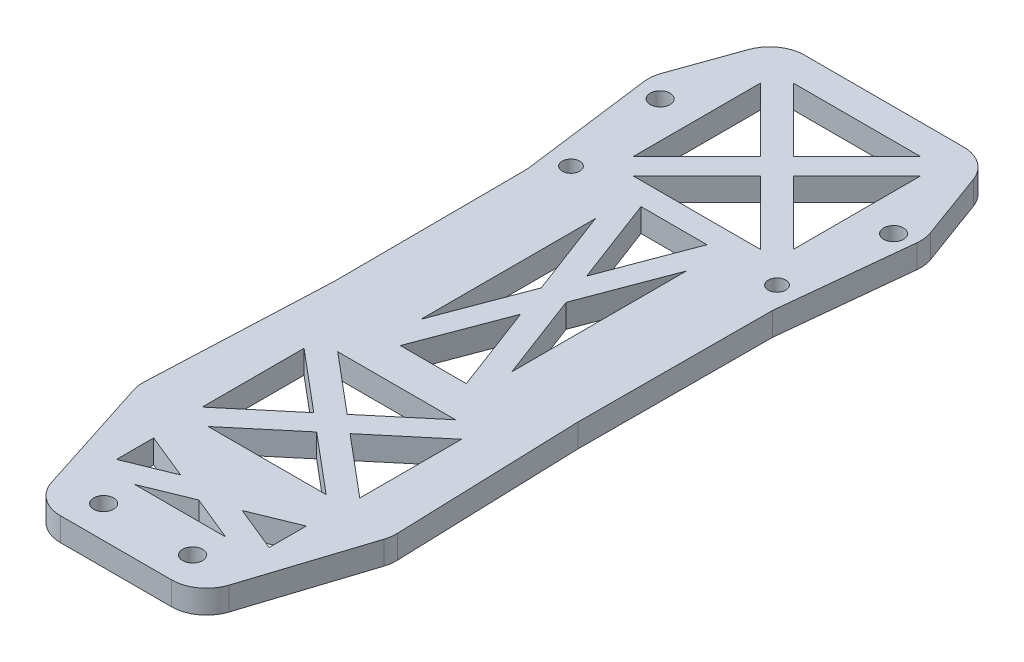
SolidWorks part; units mm, degrees
ref_plane "Front Plane" through (0, 0, 0) normal (0, 0, 1) x (1, 0, 0)
ref_plane "Top Plane" through (0, 0, 0) normal (0, 1, 0) x (1, 0, 0)
ref_plane "Right Plane" through (0, 0, 0) normal (1, 0, 0) x (0, 0, -1)
sketch "Sketch1" plane through (0, 0, 0) normal (0, 1, 0) x (1, 0, 0)
  line L12 (-13.5, 28.2668) -> (-13.5, 45.7228)
  line L13 (-13.5, 45.7228) -> (-3.1095, 36.9948)
  line L14 (-13.5, 28.2668) -> (-3.1095, 36.9948)
  line L15 (-10.1048, 48.0948) -> (0, 39.6068)
  line L16 (0, 39.6068) -> (10.1048, 48.0948)
  line L17 (-10.1048, 48.0948) -> (10.1048, 48.0948)
  line L18 (13.5, 28.2668) -> (13.5, 45.7228)
  line L19 (3.1095, 36.9948) -> (13.5, 45.7228)
  line L20 (3.1095, 36.9948) -> (13.5, 28.2668)
  line L21 (0, 34.3828) -> (10.1048, 25.8948)
  line L22 (-10.1048, 25.8948) -> (0, 34.3828)
  line L23 (-10.1048, 25.8948) -> (10.1048, 25.8948)
  line L24 (-13.0763, 19.5304) -> (-13.0763, 13.1591)
  line L25 (-13.0763, 13.1591) -> (-5.2847, 16.3448)
  line L26 (-13.0763, 19.5304) -> (-5.2847, 16.3448)
  line L27 (5.2847, 16.3448) -> (13.0763, 19.5304)
  line L28 (13.0763, 19.5304) -> (13.0763, 13.1591)
  line L29 (5.2847, 16.3448) -> (13.0763, 13.1591)
  line L30 (-7.7916, 10.9984) -> (0, 14.184)
  line L31 (0, 14.184) -> (7.7916, 10.9984)
  line L32 (-7.7916, 10.9984) -> (7.7916, 10.9984)
  line L33 (13.75, 102.3232) -> (13.75, 124.1664)
  line L34 (2.8284, 113.2448) -> (13.75, 124.1664)
  line L35 (13.75, 102.3232) -> (2.8284, 113.2448)
  line L36 (-10.9216, 99.4948) -> (10.9216, 99.4948)
  line L37 (-10.9216, 99.4948) -> (0, 110.4164)
  line L38 (10.9216, 99.4948) -> (0, 110.4164)
  line L39 (-13.75, 102.3232) -> (-2.8284, 113.2448)
  line L40 (-2.8284, 113.2448) -> (-13.75, 124.1664)
  line L41 (-13.75, 102.3232) -> (-13.75, 124.1664)
  line L42 (0, 116.0732) -> (-10.9216, 126.9948)
  line L43 (-10.9216, 126.9948) -> (10.9216, 126.9948)
  line L44 (0, 116.0732) -> (10.9216, 126.9948)
  line L45 (-7.7916, 89.9581) -> (-2.138, 74.9948)
  line L46 (-5.6536, 54.3729) -> (5.6536, 54.3729)
  line L47 (-7.7916, 60.0315) -> (-7.7916, 89.9581)
  line L48 (-5.6536, 95.6167) -> (5.6536, 95.6167)
  line L49 (7.7916, 60.0315) -> (7.7916, 89.9581)
  line L50 (-7.7916, 54.3729) -> (7.7916, 95.6167) construction
  line L51 (-7.7916, 95.6167) -> (7.7916, 54.3729) construction
  line L52 (-5.6536, 54.3729) -> (0, 69.3362)
  line L53 (-5.6536, 95.6167) -> (0, 80.6534)
  line L54 (-7.7916, 60.0315) -> (-2.138, 74.9948)
  line L55 (-5.9207, 96.3236) -> (9.6625, 55.0798) construction
  line L56 (-9.6625, 94.9098) -> (5.9207, 53.666) construction
  line L57 (-9.6625, 55.0798) -> (5.9207, 96.3236) construction
  line L58 (-5.9207, 53.666) -> (9.6625, 94.9098) construction
  line L59 (0, 69.3362) -> (5.6536, 54.3729)
  line L60 (2.138, 74.9948) -> (7.7916, 89.9581)
  line L61 (2.138, 74.9948) -> (7.7916, 60.0315)
  line L62 (0, 80.6534) -> (5.6536, 95.6167)
  line L63 (-9.5155, 0) -> (9.5155, 0)
  line L64 (-20, -0.0052) -> (20, 149.9948) construction
  line L65 (-20, 149.9948) -> (20, -0.0052) construction
  line L66 (-14.1084, 132.1078) -> (13.1312, 132.1078)
  line L69 (-19.7604, 128.1216) -> (-23.659, 117.1793)
  line L71 (-15.2273, 4.1627) -> (-21.92, 24.9687)
  line L73 (15.2273, 4.1627) -> (21.6746, 24.2059)
  line L76 (18.7641, 128.1742) -> (23.0196, 116.5735)
  line L77 (-23.9568, 114.391) -> (-20.9718, 91.4604)
  line L78 (21.0264, 91.4907) -> (23.3545, 113.8868)
  line L79 (21.9596, 26.2406) -> (20.9055, 58.256)
  line L80 (-22.2025, 27.0668) -> (-20.8394, 58.396)
  line L81 (-20.8394, 58.396) -> (-20.9718, 91.4604)
  line L82 (20.9055, 58.256) -> (21.0264, 91.4907)
  circle A4 centre (-20, 113.2448) radius 1.7
  circle A5 centre (20, 113.2448) radius 1.7
  circle A6 centre (7.62, 5.4973) radius 1.7
  circle A7 centre (-7.62, 5.4973) radius 1.7
  arc A12 (-14.1084, 132.1078) -> (-19.7604, 128.1216) centre (-14.1084, 126.1078) ccw
  arc A13 (13.1312, 132.1078) -> (18.7641, 128.1742) centre (13.1312, 126.1078) cw
  arc A14 (15.2273, 4.1627) -> (9.5155, 0) centre (9.5155, 6) cw
  arc A15 (-15.2273, 4.1627) -> (-9.5155, 0) centre (-9.5155, 6) ccw
  arc A16 (21.9596, 26.2406) -> (21.6746, 24.2059) centre (15.9628, 26.0432) cw
  arc A17 (-22.2025, 27.0668) -> (-21.92, 24.9687) centre (-16.2082, 26.806) ccw
  arc A20 (23.3545, 113.8868) -> (23.0196, 116.5735) centre (17.3867, 114.5071) ccw
  arc A23 (-23.9568, 114.391) -> (-23.659, 117.1793) centre (-18.007, 115.1656) cw
  point P70 (0, 74.9948)
  dimension "D1" = 2
  dimension "D2" = 2
extrude "Boss-Extrude1" add sketch "Sketch1" along normal blind 4
sketch "Sketch2" plane through (0, 4, 0) normal (0, 1, 0) x (1, 0, 0)
  point P0 (-7.62, 5.4973)
  point P2 (7.62, 5.4973)
  point P4 (20, 113.2448)
  point P6 (-20, 113.2448)
hole_wizard "M3 Clearance Hole1" positions "Sketch2" profile "Sketch3" hole size "M3" standard "ISO" end condition through all
sketch "Sketch3" plane through (-7.62, 4, -5.4973) normal (1, 0, 0) x (0, 0, 1)
  line L0 (0, 0) -> (0, 4)
  line L1 (0, 4) -> (1.7, 4)
  line L2 (1.7, 4) -> (1.7, 0)
  line L5 (1.7, 0) -> (0, 0)
  line L11 (0, -6.35) -> (0, 107.95) construction
  dimension "Thru Hole Dia." = 3.4
  dimension "Thru Hole Depth" = 4
sketch "Sketch4" plane through (0, 4, 0) normal (0, 1, 0) x (1, 0, 0)
  line L0 (-5.6536, 95.6167) -> (-17.6536, 95.6167) construction
  line L1 (5.6536, 95.6167) -> (17.6536, 95.6167) construction
  line L2 (-5.6536, 95.6167) -> (5.6536, 95.6167) construction
  line L3 (0, 80.6534) -> (5.6536, 95.6167) construction
  circle A0 centre (-17.6536, 95.6167) radius 1.5
  circle A1 centre (17.6536, 95.6167) radius 1.5
  dimension "D3" = 3
  dimension "D4" = 3
  dimension "D1" = 12
  dimension "D2" = 12
extrude "Cut-Extrude1" cut sketch "Sketch4" against normal through all contours A0 | A1
